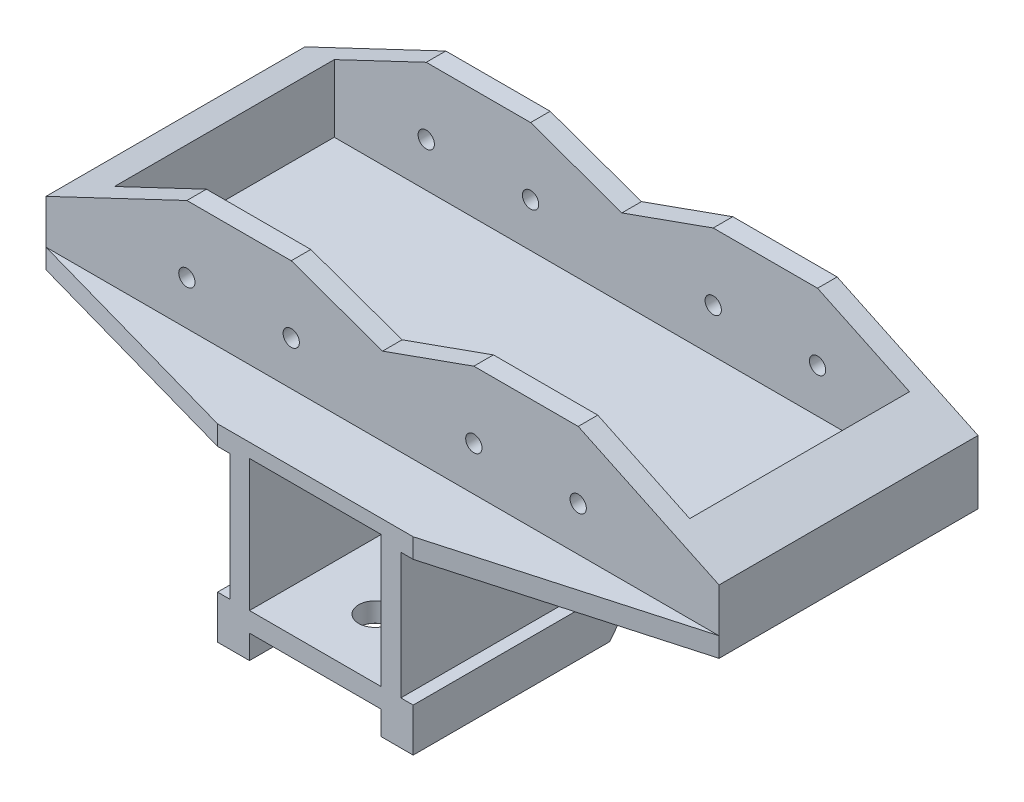
SolidWorks part; units mm, degrees
ref_plane "前视基准面" through (0, 0, 0) normal (0, 0, 1) x (1, 0, 0)
ref_plane "上视基准面" through (0, 0, 0) normal (0, 1, 0) x (1, 0, 0)
ref_plane "右视基准面" through (0, 0, 0) normal (1, 0, 0) x (0, 0, -1)
sketch "草图1" plane through (0, 0, 0) normal (0, 0, 1) x (1, 0, 0)
  line L0 (0, 0) -> (-103.2, 0)
  line L1 (-103.2, 0) -> (-103.2, 20)
  line L2 (-103.2, 20) -> (0, 20)
  line L3 (0, 20) -> (0, 0)
  dimension "D1" = 103.2
  dimension "D2" = 20
extrude "凸台-拉伸1" add sketch "草图1" along normal blind 39.7
sketch "草图2" plane through (0, 20, 0) normal (0, 1, 0) x (1, 0, 0)
  line L0 (-51.6, 0) -> (-51.6, -39.7) construction
  line L2 (-99.2, -19.85) -> (-72.6862, -19.85) construction
  line L5 (-95.7, -3) -> (-7.5, -3)
  line L6 (-95.7, -3) -> (-95.7, -36.7)
  line L7 (-95.7, -36.7) -> (-7.5, -36.7)
  line L8 (-7.5, -3) -> (-7.5, -36.7)
  dimension "D1" = 88.2
  dimension "D2" = 33.7
extrude "切除-拉伸1" cut sketch "草图2" against normal offset from surface (17 mm away) 3 up to face at (-51.6, 0, 19.85)
sketch "草图3" plane through (0, 0, 0) normal (0, -1, 0) x (1, 0, 0)
  line L6 (-51.6, 39.7) -> (-51.6, -13.7739) construction
  line L11 (-103.2, 0) -> (0, 0) construction
  line L12 (-66.6, 0) -> (-36.6, 0)
  line L15 (-66.6, 0) -> (-66.6, 50)
  line L16 (-66.6, 50) -> (-36.6, 50)
  line L17 (-36.6, 50) -> (-36.6, 0)
  point P11 (-51.6, 0)
  dimension "D1" = 50
  dimension "D2" = 15
extrude "凸台-拉伸2" add sketch "草图3" along normal blind 29 from offset 3 offset against normal yes
sketch "草图21" plane through (0, 0, 50) normal (0, 0, 1) x (1, 0, 0)
  line L0 (-7.5, 3) -> (-95.7, 3) construction
  line L1 (-7.5, 3) -> (-95.7, 3) construction
  line L2 (-98.033, -9.25) -> (-9.0097, -9.25) construction
  line L3 (-51.6, -26) -> (-51.6, 30.6239) construction
  line L4 (-61.7, 0.85) -> (-41.5, 0.85)
  line L5 (-61.7, 0.85) -> (-61.7, -19.35)
  line L6 (-61.7, -19.35) -> (-41.5, -19.35)
  line L7 (-41.5, 0.85) -> (-41.5, -19.35)
  dimension "D1" = 12.25
  dimension "D2" = 20.2
  dimension "D3" = 20.2
extrude "切除-拉伸11" cut sketch "草图21" against normal offset from surface (30.15 mm away) 19.85 up to face at (-51.6, -1.5, 0)
sketch "草图22" plane through (0, -26, 0) normal (0, -1, 0) x (1, 0, 0)
  line L1 (-61.7, 50) -> (-41.5, 50)
  line L2 (-41.5, 50) -> (-41.5, 0)
  line L3 (-66.6, 0) -> (-36.6, 0) construction
  line L4 (-41.5, 0) -> (-61.7, 0)
  line L5 (-61.7, 0) -> (-61.7, 50)
  line L6 (-36.6, 50) -> (-66.6, 50) construction
  dimension "D1" = 0
extrude "切除-拉伸12" cut sketch "草图22" against normal offset from surface (3.65 mm away) 3 up to face at (-51.6, -19.35, 34.925)
sketch "草图24" plane through (-36.6, 0, 0) normal (1, 0, 0) x (0, 0, -1)
  line L0 (0, 0) -> (0, -26)
  line L1 (0, -26) -> (-19.85, -26)
  line L2 (0, -26) -> (-50, -26) construction
  line L3 (-19.85, -26) -> (0, 0)
  line L4 (-19.85, -19.35) -> (-19.85, 0.85) construction
  line L5 (-19.85, -19.35) -> (-19.85, 0.85) construction
extrude "切除-拉伸14" cut sketch "草图24" against normal through all
sketch "草图25" plane through (0, 0, 0) normal (0, -1, 0) x (1, 0, 0)
  line L0 (-36.6, 39.7) -> (-36.6, 50)
  line L1 (-36.6, 50) -> (0, 39.7)
  line L2 (-51.6, 50) -> (-51.6, 41.294) construction
  line L4 (-36.6, 39.7) -> (0, 39.7)
  line L5 (-66.6, 39.7) -> (-103.2, 39.7)
  line L6 (-66.6, 50) -> (-103.2, 39.7)
  line L7 (-66.6, 39.7) -> (-66.6, 50)
extrude "凸台-拉伸4" add sketch "草图25" against normal up to surface (3 mm away) up to face at (-51.6, 3, 44.85)
hole_wizard "Ø2.5mm 暗销孔2" positions "草图26" profile "草图27" hole size "Ø2.5" standard "ISO" end condition through all
sketch "草图26" plane through (0, 0, 0) normal (0, 0, -1) x (-1, 0, 0)
  line L0 (-4.2264, 3) -> (108.8141, 3) construction
  line L2 (36.6, 0) -> (0, 0) construction
  line L3 (51.6, 0) -> (51.6, 22.298) construction
  point P8 (37.6, 9.75)
  point P10 (21.6, 9.75)
  point P23 (65.6, 9.75)
  point P24 (81.6, 9.75)
  dimension "D1" = 3
  dimension "D2" = 14
  dimension "D3" = 16
  dimension "D4" = 6.75
  dimension "D5" = 6.75
sketch "草图27" plane through (-81.6, 9.75, 0) normal (1, 0, 0) x (0, 1, 0)
  line L0 (0, 0) -> (0, 50)
  line L1 (0, 50) -> (1.25, 50)
  line L2 (1.25, 50) -> (1.25, 0.025)
  line L3 (1.25, 0.025) -> (1.275, 0)
  line L5 (1.275, 0) -> (0, 0)
  line L6 (-1.25, 0.025) -> (-1.275, 0) construction
  line L11 (0, -6.35) -> (0, 107.95) construction
  dimension "通孔孔直径" = 2.5
  dimension "通孔孔深度" = 50
  dimension "近端锥形沉头孔直径" = 2.55
  dimension "近端锥形沉头孔角度" = 90
hole_wizard "Ø5.0mm 暗销孔3" positions "草图28" profile "草图29" hole size "Ø5.0" standard "ISO"
sketch "草图28" plane through (0, -22.35, 0) normal (0, -1, 0) x (-1, 0, 0)
  line L0 (51.6, -17.0634) -> (51.6, -50) construction
  line L4 (41.5, -19.85) -> (61.7, -19.85) construction
  point P19 (51.6, -25.85)
  point P21 (51.6, -40.85)
  dimension "D1" = 6
  dimension "D2" = 15
sketch "草图29" plane through (-51.6, -22.35, 40.85) normal (1, 0, 0) x (0, 0, -1)
  line L0 (0, 0) -> (0, 3)
  line L1 (0, 3) -> (2.5, 3)
  line L2 (2.5, 3) -> (2.5, 0.025)
  line L3 (2.5, 0.025) -> (2.525, 0)
  line L5 (2.525, 0) -> (0, 0)
  line L6 (-2.5, 0.025) -> (-2.525, 0) construction
  line L11 (0, -6.35) -> (0, 107.95) construction
  dimension "通孔孔直径" = 5
  dimension "通孔孔深度" = 3
  dimension "近端锥形沉头孔直径" = 5.05
  dimension "近端锥形沉头孔角度" = 90
sketch "草图30" plane through (-36.6, 0, 0) normal (1, 0, 0) x (0, 0, -1)
  line L0 (0, 0) -> (-50, 0) construction
  line L1 (-50, 0) -> (2.5209, 0)
  line L4 (-50, -19.35) -> (-19.85, -19.35)
  line L5 (-50, 0.85) -> (-50, -19.35)
  line L6 (-19.85, 0.85) -> (-50, 0.85)
  line L7 (-19.85, -19.35) -> (-19.85, 0.85)
  line L8 (-50, -19.35) -> (2.5209, -19.35)
  line L9 (-50, 0) -> (-50, -19.35)
  line L11 (2.5209, -19.35) -> (2.5209, 0)
  dimension "D1" = 0
extrude "切除-拉伸15" cut sketch "草图30" against normal offset from surface (1.9 mm away) 3 up to face at (-41.5, -9.25, 34.925)
sketch "草图31" plane through (-66.6, 0, 0) normal (-1, 0, 0) x (0, 0, 1)
  line L4 (0, 0) -> (14.773, -19.35)
  line L5 (50, 0) -> (0, 0)
  line L6 (50, -19.35) -> (50, 0)
  line L7 (14.773, -19.35) -> (50, -19.35)
  line L8 (0, 0) -> (14.773, -19.35)
  line L9 (50, 0) -> (0, 0)
  line L10 (50, -19.35) -> (50, 0)
  line L11 (14.773, -19.35) -> (50, -19.35)
  dimension "D1" = 0
extrude "切除-拉伸16" cut sketch "草图31" against normal offset from surface (1.9 mm away) 3 up to face at (-61.7, -9.25, 34.925)
hole_wizard "Ø5.0mm 暗销孔4" positions "草图34" profile "草图33" hole size "Ø5.0" standard "ISO" end condition through all
sketch "草图34" plane through (-38.5, 0, 0) normal (1, 0, 0) x (0, 0, -1)
  line L2 (-43.9538, -9.25) -> (-19.6706, -9.25) construction
  line L5 (-19.85, 0.85) -> (-19.85, -19.35) construction
  point P10 (-25.85, -9.25)
  dimension "D1" = 6
sketch "草图33" plane through (-38.5, -9.25, 25.85) normal (0, 1, 0) x (0, 0, -1)
  line L0 (0, 0) -> (0, 64.7)
  line L1 (0, 64.7) -> (2.5, 64.7)
  line L2 (2.5, 64.7) -> (2.5, 0.025)
  line L3 (2.5, 0.025) -> (2.525, 0)
  line L5 (2.525, 0) -> (0, 0)
  line L6 (-2.5, 0.025) -> (-2.525, 0) construction
  line L11 (0, -6.35) -> (0, 107.95) construction
  dimension "通孔孔直径" = 5
  dimension "通孔孔深度" = 64.7
  dimension "近端锥形沉头孔直径" = 5.05
  dimension "近端锥形沉头孔角度" = 90
sketch "草图35" plane through (0, 0, 0) normal (0, 0, -1) x (-1, 0, 0)
  line L0 (21.6, 9.75) -> (37.6, 9.75) construction
  line L1 (21.6, 9.75) -> (21.6, 21.6918) construction
  line L2 (37.6, 9.75) -> (37.6, 21.6918) construction
  line L3 (0, 9.75) -> (21.6, 20)
  line L4 (0, 0) -> (0, 20) construction
  line L5 (21.6, 20) -> (0, 20)
  line L6 (0, 20) -> (0, 9.75)
  line L7 (0, 20) -> (103.2, 20) construction
  line L8 (51.6, 0) -> (51.6, 24.4852) construction
  line L10 (37.6, 20) -> (51.6, 15)
  line L11 (51.6, 15) -> (51.6, 20)
  line L12 (65.6, 20) -> (37.6, 20)
  line L13 (81.6, 20) -> (103.2, 20)
  line L14 (103.2, 9.75) -> (81.6, 20)
  line L15 (103.2, 20) -> (103.2, 9.75)
  line L16 (65.6, 20) -> (51.6, 15)
  line M17 (103.2, 0) -> (103.2, 20)
  line M18 (103.2, 20) -> (0, 20)
  dimension "D1" = 5
extrude "切除-拉伸19" cut sketch "草图35" against normal through all contours L14 M17 M18 | L6 L3 L5 | L16 L12 L10
hole_wizard "Ø2.5mm 暗销孔1" positions "草图9" profile "草图10" hole size "Ø2.5" standard "ISO" end condition through all
sketch "草图9" plane through (0, 0, 0) normal (0, 0, -1) x (-1, 0, 0)
  line L0 (51.6, 20) -> (51.6, -22.35) construction
  line L1 (24.6288, 3) -> (104.6858, 3) construction
  line L3 (38.5, 0) -> (0, 0) construction
  point P25 (37.6, 9.75)
  point P27 (21.6, 9.75)
  point P30 (65.6, 9.75)
  point P31 (81.6, 9.75)
  dimension "D1" = 3
  dimension "D2" = 14
  dimension "D3" = 16
  dimension "D4" = 6.75
  dimension "D5" = 6.75
sketch "草图10" plane through (-81.6, 9.75, 0) normal (1, 0, 0) x (0, 1, 0)
  line L0 (0, 0) -> (0, 50)
  line L1 (0, 50) -> (1.25, 50)
  line L2 (1.25, 50) -> (1.25, 0.025)
  line L3 (1.25, 0.025) -> (1.275, 0)
  line L5 (1.275, 0) -> (0, 0)
  line L6 (-1.25, 0.025) -> (-1.275, 0) construction
  line L11 (0, -6.35) -> (0, 107.95) construction
  dimension "通孔孔直径" = 2.5
  dimension "通孔孔深度" = 50
  dimension "近端锥形沉头孔直径" = 2.55
  dimension "近端锥形沉头孔角度" = 90
